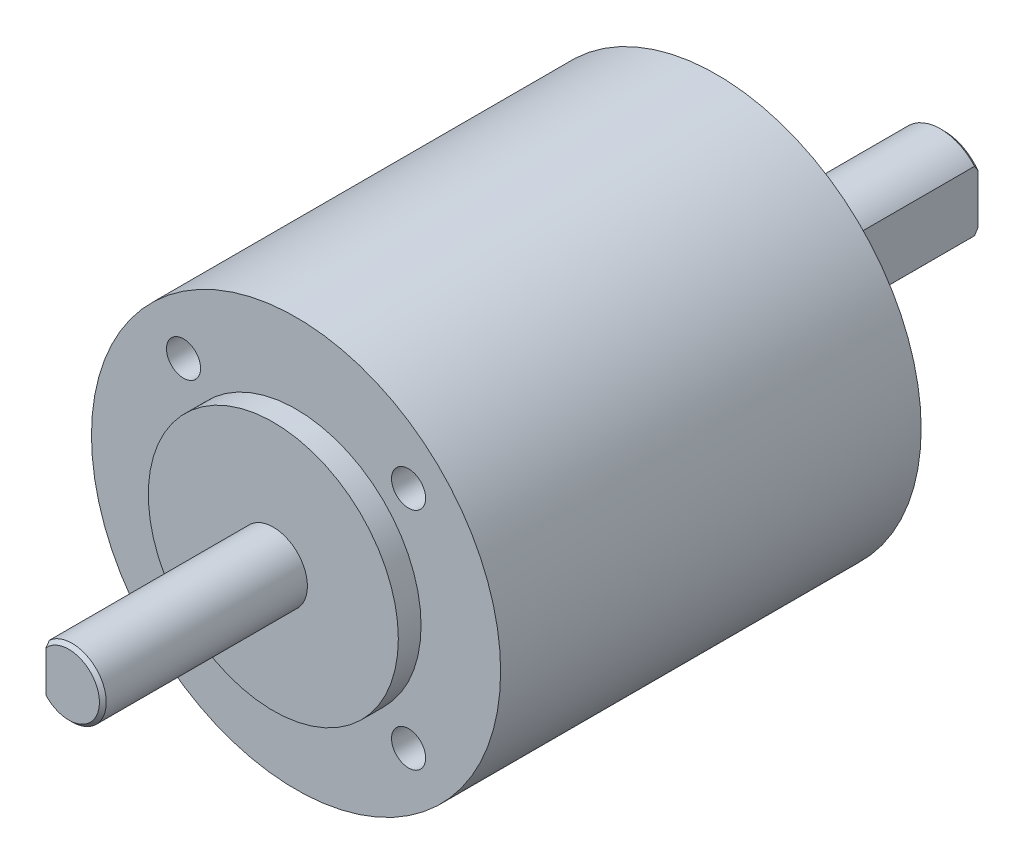
SolidWorks part; units mm, degrees
other "标注1"
sketch "草图10" plane through (18, -18, 38.5) normal (0.8492, -0.0046, 0.5281) x (0.52, 0.182, -0.8346)
material "6061 合金"
ref_plane "前视基准面" through (0, 0, 0) normal (0, 0, 1) x (1, 0, 0)
ref_plane "上视基准面" through (0, 0, 0) normal (0, 1, 0) x (1, 0, 0)
ref_plane "右视基准面" through (0, 0, 0) normal (1, 0, 0) x (0, 0, -1)
sketch "草图1" plane through (0, 0, 0) normal (0, 0, 1) x (1, 0, 0)
  circle A0 centre (0, 0) radius 18
extrude "凸台-拉伸1" add sketch "草图1" against normal mid plane 37
sketch "草图2" plane through (0, 0, 18.5) normal (0, 0, 1) x (1, 0, 0)
  circle A0 centre (0, 0) radius 3
extrude "凸台-拉伸2" add sketch "草图2" along normal blind 20
sketch "草图3" plane through (0, 0, 18.5) normal (0, 0, 1) x (1, 0, 0)
  circle A0 centre (0, 0) radius 11
extrude "凸台-拉伸3" add sketch "草图3" along normal blind 2
sketch "草图4" plane through (0, 0, 18.5) normal (0, 0, 1) x (1, 0, 0)
  line L0 (0, 0) -> (-14.506, 14.506) construction
  circle A0 centre (0, 0) radius 14 construction
  circle A1 centre (-9.8995, 9.8995) radius 1.5
  circle A2 centre (9.8995, 9.8995) radius 1.5
  circle A3 centre (9.8995, -9.8995) radius 1.5
  circle A4 centre (-9.8995, -9.8995) radius 1.5
  point P15 (0, 0)
  dimension "D1" = 4
extrude "切除-拉伸1" cut sketch "草图4" against normal blind 8
sketch "草图5" plane through (0, 0, -18.5) normal (0, 0, -1) x (-1, 0, 0)
  circle A0 centre (0, 0) radius 4
extrude "凸台-拉伸4" add sketch "草图5" along normal blind 20
sketch "草图6" plane through (0, 0, -18.5) normal (0, 0, -1) x (-1, 0, 0)
  circle A0 centre (0, 0) radius 11
extrude "凸台-拉伸5" add sketch "草图6" along normal blind 2
sketch "草图7" plane through (0, 0, -18.5) normal (0, 0, -1) x (-1, 0, 0)
  line L0 (0, 0) -> (-16.0575, 16.0575) construction
  circle A0 centre (0, 0) radius 14 construction
  circle A1 centre (-9.8995, 9.8995) radius 1.5
  circle A2 centre (9.8995, 9.8995) radius 1.5
  circle A3 centre (9.8995, -9.8995) radius 1.5
  circle A4 centre (-9.8995, -9.8995) radius 1.5
  point P15 (0, 0)
  dimension "D1" = 4
extrude "切除-拉伸2" cut sketch "草图7" against normal blind 8
sketch "草图8" plane through (0, 0, 38.5) normal (0, 0, 1) x (1, 0, 0)
  line L0 (0, 0) -> (-2, 0) construction
  line L2 (-2, 2.2361) -> (-2, -2.2361)
  circle A2 centre (0, 0) radius 3 construction
  arc A3 (-2, 2.2361) -> (-2, -2.2361) centre (0, 0) ccw
extrude "切除-拉伸3" cut sketch "草图8" against normal blind 15
sketch "草图9" plane through (0, 0, -38.5) normal (0, 0, -1) x (-1, 0, 0)
  line L0 (0, 0) -> (-3, 0) construction
  line L2 (-3, 2.6458) -> (-3, -2.6458)
  circle A2 centre (0, 0) radius 4 construction
  arc A3 (-3, 2.6458) -> (-3, -2.6458) centre (0, 0) ccw
extrude "切除-拉伸4" cut sketch "草图9" against normal blind 15
chamfer "倒角1" distance 0.3 angle 45 2 edges at (-4, 0, -38.5) (3, 0, 38.5)
